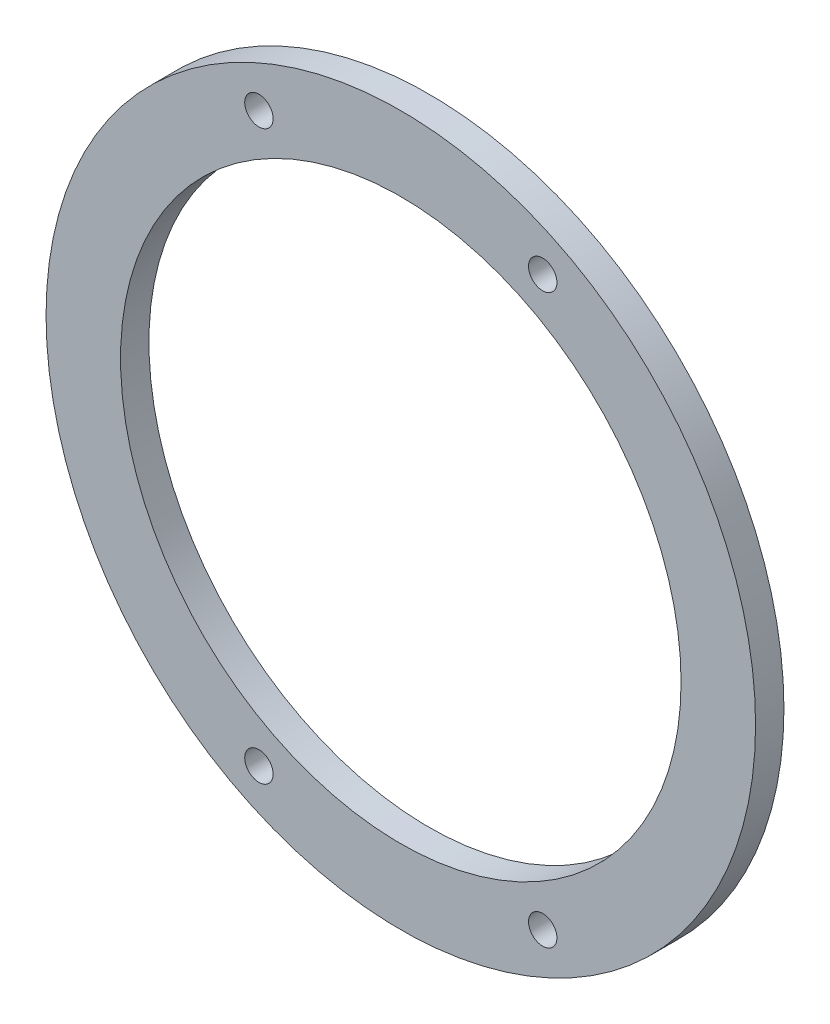
SolidWorks part; units mm, degrees
ref_plane "前视基准面" through (0, 0, 0) normal (0, 0, 1) x (1, 0, 0)
ref_plane "上视基准面" through (0, 0, 0) normal (0, 1, 0) x (1, 0, 0)
ref_plane "右视基准面" through (0, 0, 0) normal (1, 0, 0) x (0, 0, -1)
sketch "草图1" plane through (0, 0, 0) normal (0, 0, 1) x (1, 0, 0)
  line L0 (0, -1.8543) -> (0, -21.8543) construction
  line L1 (0, -21.8543) -> (-20, -21.8543) construction
  line L2 (0, -1.8543) -> (0, 64.1457) construction
  circle A0 centre (0, -1.8543) radius 10 construction
  circle A1 centre (0, -21.8543) radius 4.5 construction
  circle A2 centre (-20, -21.8543) radius 2 construction
  circle A3 centre (-20, 18.1457) radius 2
  circle A4 centre (20, 18.1457) radius 2
  circle A5 centre (20, -21.8543) radius 2 construction
  circle A6 centre (20, -61.8543) radius 2
  circle A7 centre (-20, -61.8543) radius 2
  circle A8 centre (0, -21.8543) radius 39.5
  circle A9 centre (0, -21.8543) radius 50
extrude "凸台-拉伸1" add sketch "草图1" along normal blind 4 contours A8
